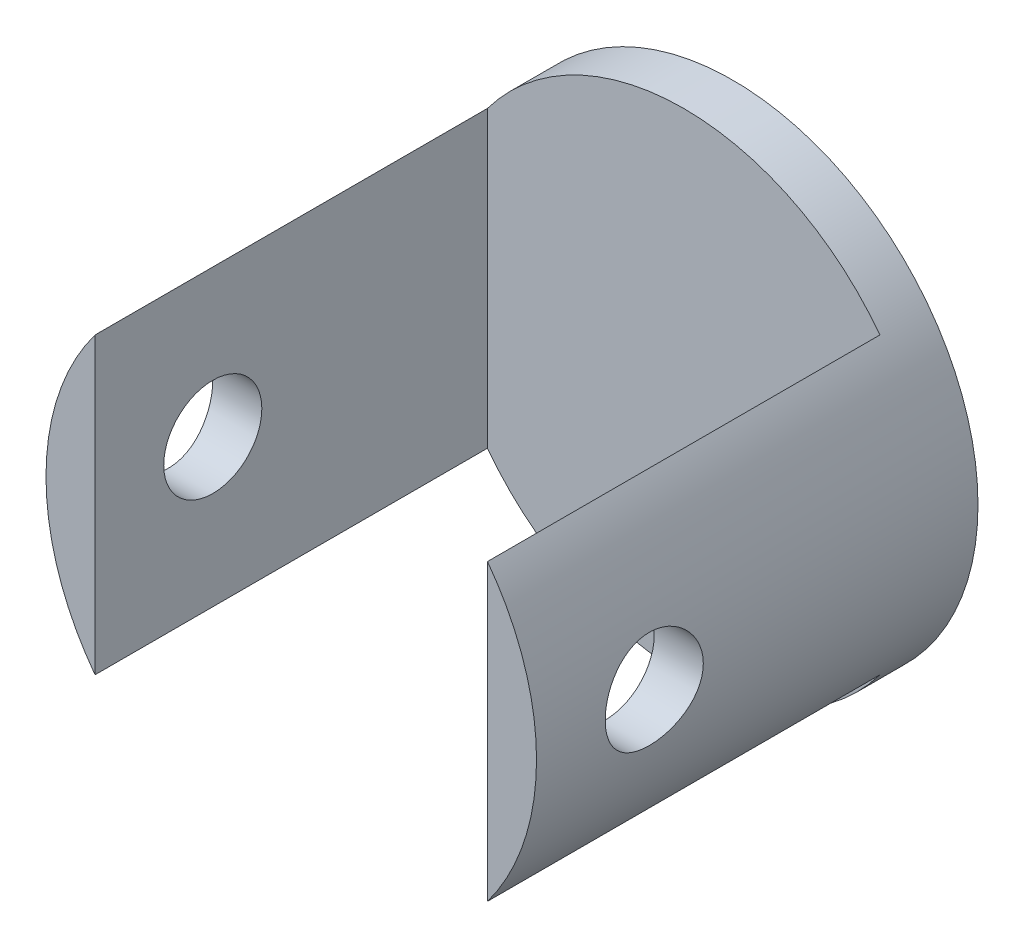
SolidWorks part; units mm, degrees
ref_plane "Ön Düzlem" through (0, 0, 0) normal (0, 0, 1) x (1, 0, 0)
ref_plane "Üst Düzlem" through (0, 0, 0) normal (0, 1, 0) x (1, 0, 0)
ref_plane "Sağ Düzlem" through (0, 0, 0) normal (1, 0, 0) x (0, 0, -1)
sketch "Sketch1" plane through (0, 0, 0) normal (0, 0, 1) x (1, 0, 0)
  circle A0 centre (0, 0) radius 25
  dimension "D1" = 50
extrude "Boss-Extrude1" add sketch "Sketch1" along normal blind 45
sketch "Sketch2" plane through (0, 0, 45) normal (0, 0, 1) x (1, 0, 0)
  line L0 (-20, 15) -> (-20, -15)
  line L1 (20, 15) -> (20, -15)
  line L2 (0, 25) -> (0, -25) construction
  line L3 (-20, 0) -> (20, 0) construction
  arc A1 (20, 15) -> (-20, 15) centre (0, 0) ccw
  circle A2 centre (0, 0) radius 25
  arc A3 (-20, -15) -> (20, -15) centre (0, 0) ccw
  dimension "D2" = 20
  dimension "D3" = 20
  dimension "D1" = 0
extrude "Cut-Extrude1" cut sketch "Sketch2" against normal blind 40
sketch "Sketch3" plane through (0, 0, 0) normal (0, 0, -1) x (-1, 0, 0)
  line L0 (0, 25) -> (0, -25) construction
  line L1 (-25, 0) -> (25, 0) construction
  circle A0 centre (0, 0) radius 25 construction
  circle A1 centre (6.33, 7.66) radius 5
  circle A2 centre (-6.33, -7.66) radius 5
  dimension "D5" = 10
  dimension "D1" = 6.33
  dimension "D2" = 6.33
  dimension "D3" = 7.66
  dimension "D4" = 7.66
extrude "Boss-Extrude2" add sketch "Sketch3" along normal blind 2
sketch "Sketch4" plane through (-20, 0, 0) normal (1, 0, 0) x (0, 0, -1)
  line L0 (-45, 15) -> (-45, -15) construction
  line L1 (0, 0) -> (-45, 0) construction
  circle A0 centre (-33, 0) radius 5
  dimension "D1" = 10
  dimension "D2" = 12
extrude "Cut-Extrude2" cut sketch "Sketch4" against normal through all and the other way through all
